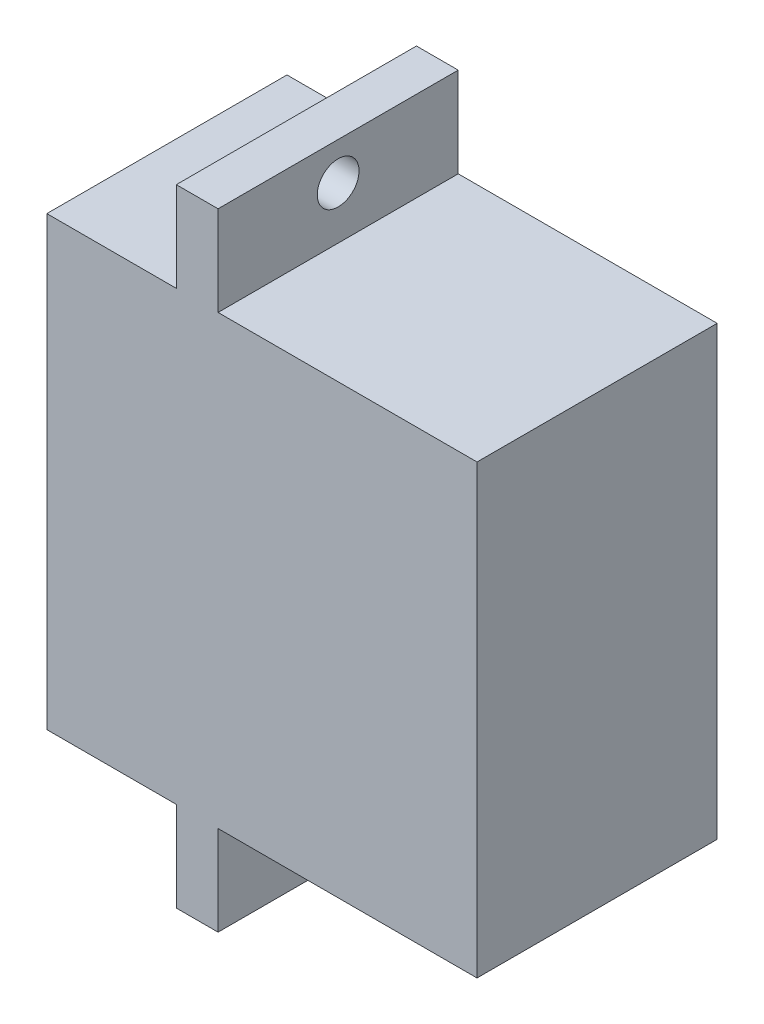
SolidWorks part; units mm, degrees
ref_plane "前视基准面" through (0, 0, 0) normal (0, 0, 1) x (1, 0, 0)
ref_plane "上视基准面" through (0, 0, 0) normal (0, 1, 0) x (1, 0, 0)
ref_plane "右视基准面" through (0, 0, 0) normal (1, 0, 0) x (0, 0, -1)
sketch "草图1" plane through (0, 0, 0) normal (1, 0, 0) x (0, 0, -1)
  line L1 (-2.25, -15.65) -> (9.25, -15.65)
  line L2 (-2.25, -15.65) -> (-2.25, 5.75)
  line L3 (-2.25, 5.75) -> (9.25, 5.75)
  line L4 (9.25, -15.65) -> (9.25, 5.75)
extrude "机身21.4x11.5_总高20.6" add sketch "草图1" along normal blind 20.6 from offset 29.8
sketch "草图2" plane through (0, 0, 0) normal (1, 0, 0) x (0, 0, -1)
  line L1 (-2.25, -19.95) -> (9.25, -19.95)
  line L2 (-2.25, -19.95) -> (-2.25, 10.05)
  line L3 (-2.25, 10.05) -> (9.25, 10.05)
  line L4 (9.25, -19.95) -> (9.25, 10.05)
  circle A0 centre (3.5, -18.15) radius 1
  circle A1 centre (3.5, 8.25) radius 1
extrude "安装耳30_孔距26.4_孔径2_耳厚暂定2" add sketch "草图2" along normal blind 2 from offset 36
sketch "草图3" plane through (0, 0, 0) normal (1, 0, 0) x (0, 0, -1)
  circle A0 centre (3.5, 0) radius 2.5
extrude "输出齿轴简化_直径5高2.8待实测" add sketch "草图3" along normal blind 2.8 from offset 27
